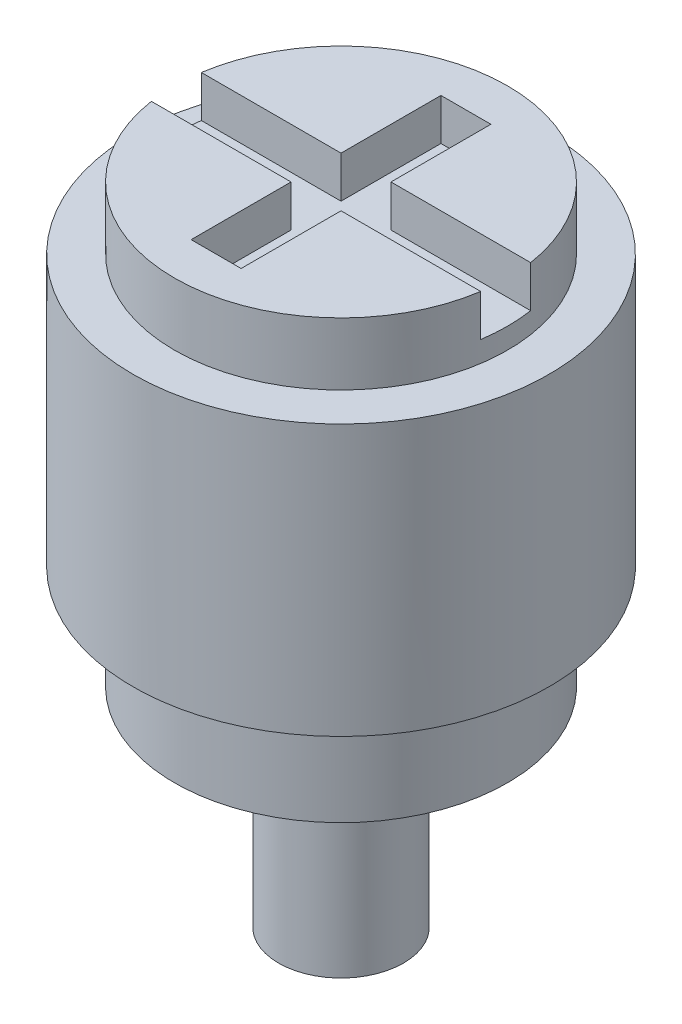
SolidWorks part; units mm, degrees
ref_plane "前视基准面" through (0, 0, 0) normal (0, 0, 1) x (1, 0, 0)
ref_plane "上视基准面" through (0, 0, 0) normal (0, 1, 0) x (1, 0, 0)
ref_plane "右视基准面" through (0, 0, 0) normal (1, 0, 0) x (0, 0, -1)
sketch "草图1" plane through (0, 0, 0) normal (0, 1, 0) x (1, 0, 0)
  circle A0 centre (0, 0) radius 1.5
  dimension "D1" = 3
extrude "拉伸1" add sketch "草图1" along normal blind 5
sketch "草图6" plane through (0, 5, 0) normal (0, 1, 0) x (1, 0, 0)
  circle A0 centre (0, 0) radius 5
  dimension "D1" = 10
extrude "凸台-拉伸1" add sketch "草图6" along normal blind 9
sketch "草图2" plane through (0, 14, 0) normal (0, 1, 0) x (-1, 0, 0)
  circle A0 centre (0, 0) radius 4
  dimension "D1" = 8
extrude "拉伸2" add sketch "草图2" along normal blind 1.5
sketch "草图3" plane through (0, 15.5, 0) normal (0, 1, 0) x (-1, 0, 0)
  line L0 (4.0624, 0) -> (-4.2778, 0) construction
  line L1 (0, -3.5166) -> (0, 3.738) construction
  line L3 (4.1821, -0.6) -> (-4.1821, -0.6)
  line L4 (4.1821, -0.6) -> (4.1821, 0.6)
  line L5 (4.1821, 0.6) -> (-4.1821, 0.6)
  line L6 (-4.1821, -0.6) -> (-4.1821, 0.6)
  dimension "D1" = 1.2
extrude "切除-拉伸1" cut sketch "草图3" against normal blind 1
sketch "草图4" plane through (0, 15.5, 0) normal (0, 1, 0) x (-1, 0, 0)
  line L0 (0, -3.8639) -> (0, 3.6765) construction
  line L1 (1.7727, 0) -> (-1.7019, 0) construction
  line L2 (0.6, -3) -> (-0.6, -3)
  line L3 (0.6, -3) -> (0.6, 3)
  line L4 (0.6, 3) -> (-0.6, 3)
  line L5 (-0.6, -3) -> (-0.6, 3)
  dimension "D1" = 1.2
  dimension "D2" = 6
extrude "切除-拉伸2" cut sketch "草图4" against normal blind 1
sketch "草图7" plane through (0, 5, 0) normal (0, -1, 0) x (1, 0, 0)
  circle A0 centre (0, 0) radius 1.5 construction
  circle A1 centre (0, 0) radius 1.5
  circle A2 centre (0, 0) radius 3
  dimension "D1" = 6
extrude "切除-拉伸3" cut sketch "草图7" against normal blind 2
sketch "草图8" plane through (0, 5, 0) normal (0, -1, 0) x (-1, 0, 0)
  circle A0 centre (0, 0) radius 4
  dimension "D1" = 8
extrude "切除-拉伸4" cut sketch "草图8" against normal blind 2.5 flip side to cut
